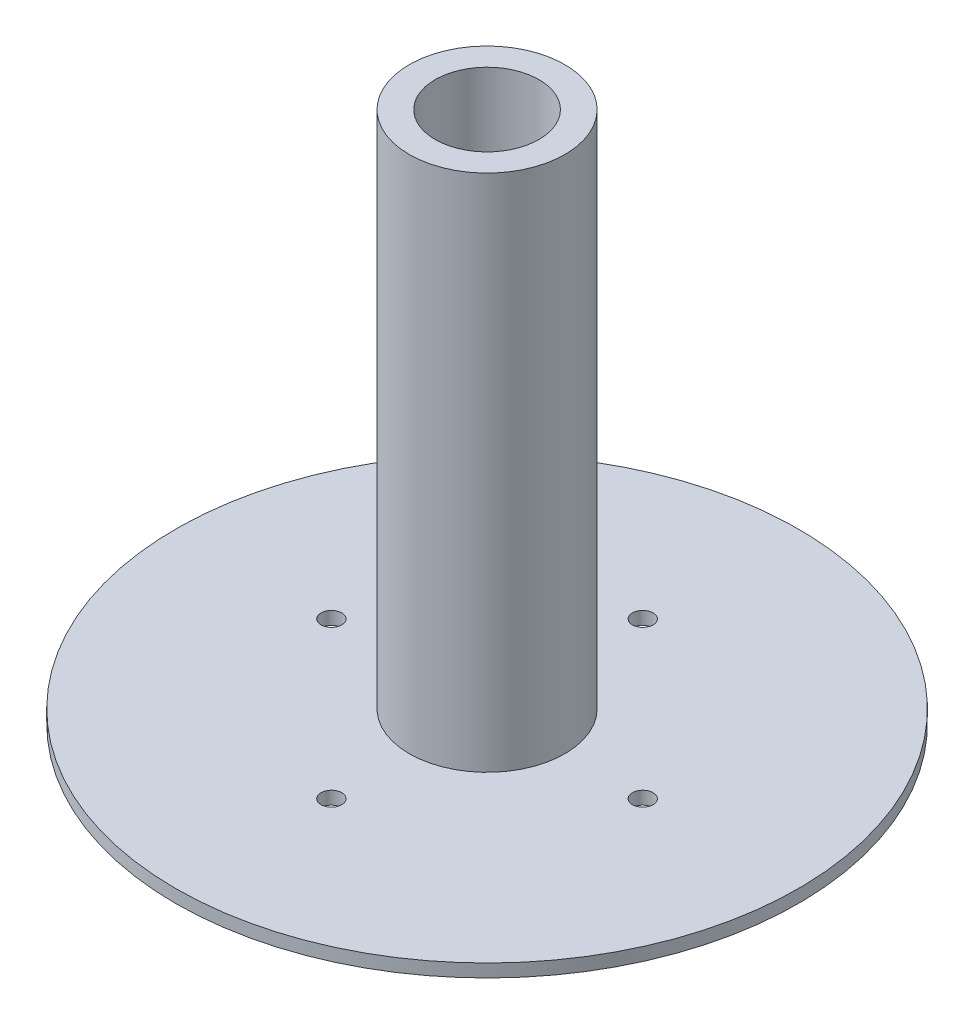
SolidWorks part; units mm, degrees
ref_plane "前视基准面" through (0, 0, 0) normal (0, 0, 1) x (1, 0, 0)
ref_plane "上视基准面" through (0, 0, 0) normal (0, 1, 0) x (1, 0, 0)
ref_plane "右视基准面" through (0, 0, 0) normal (1, 0, 0) x (0, 0, -1)
sketch "草图1" plane through (0, 0, 0) normal (0, 1, 0) x (1, 0, 0)
  circle A0 centre (0, 0) radius 120
extrude "凸台-拉伸1" add sketch "草图1" along normal blind 5
sketch "草图2" plane through (0, 5, 0) normal (0, 1, 0) x (1, 0, 0)
  line L0 (0, 105.2282) -> (0, -107.7804) construction
  line L3 (124.0741, 0) -> (-124.0527, 0) construction
  circle A0 centre (0, 0) radius 60
hole_wizard "大小mm 暗销孔2" positions "3D草图2" profile "草图5" hole size "Ø8.0" standard "ISO"
sketch3d "3D草图2"
  line L0 (0, 5, -105.2282) -> (0, 5, 107.7804) construction
  line L1 (124.0741, 5, 0) -> (-124.0527, 5, 0) construction
  circle A0 centre (0, 5, 0) radius 60 construction
  point P0 (0, 5, -60)
  point P4 (0, 65, 0)
  point P7 (-60, 5, 0)
  point P11 (0, 5, 60)
  point P13 (60, 5, 0)
sketch "草图5" plane through (0, 5, -60) normal (1, 0, 0) x (0, 0, 1)
  line L0 (0, 0) -> (0, 22.4034)
  line L1 (0, 22.4034) -> (4, 20)
  line L2 (4, 20) -> (4, 0)
  line L5 (4, 0) -> (0, 0)
  line L10 (0, 22.4034) -> (-4, 20) construction
  line L11 (0, -6.35) -> (0, 107.95) construction
  dimension "孔直径" = 8
  dimension "孔深度" = 20
  dimension "导头角度" = 118
sketch "草图6" plane through (0, 5, 0) normal (0, 1, 0) x (1, 0, 0)
  circle A0 centre (0, 0) radius 20
  circle A1 centre (0, 0) radius 30
extrude "凸台-拉伸2" add sketch "草图6" along normal blind 200
sketch "草图7" plane through (0, 0, 0) normal (0, 0, 1) x (1, 0, 0)
  line L0 (0, 159.3561) -> (0, -8.1599) construction
